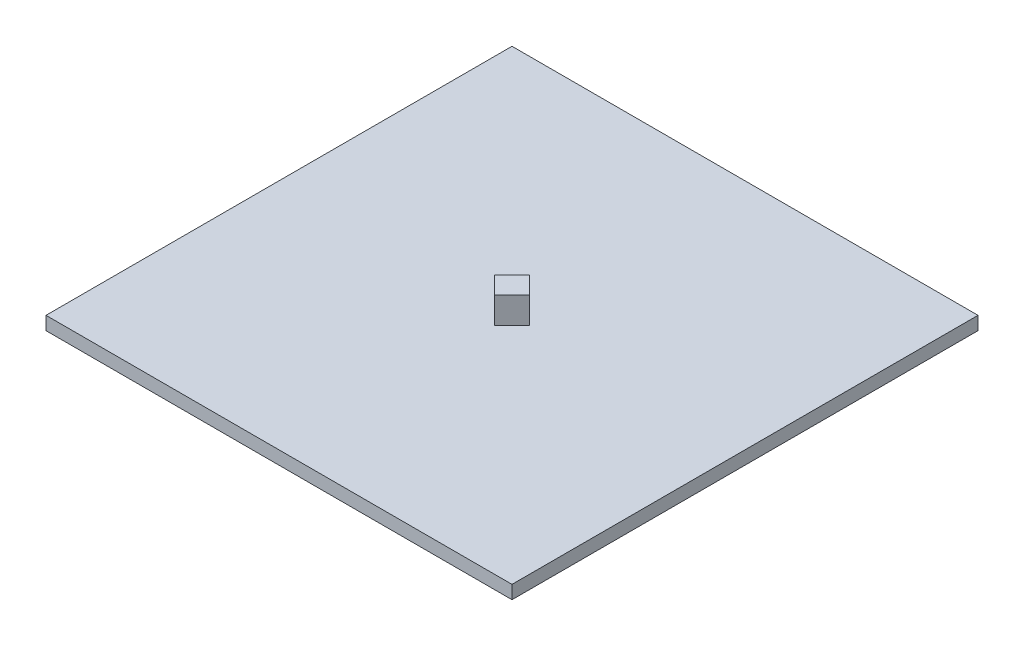
SolidWorks part; units mm, degrees
ref_plane "Front Plane" through (0, 0, 0) normal (0, 0, 1) x (1, 0, 0)
ref_plane "Top Plane" through (0, 0, 0) normal (0, 1, 0) x (1, 0, 0)
ref_plane "Right Plane" through (0, 0, 0) normal (1, 0, 0) x (0, 0, -1)
sketch "Sketch1" plane through (0, 0, 0) normal (0, 1, 0) x (1, 0, 0)
  line L1 (-44.45, -44.45) -> (44.45, -44.45)
  line L2 (-44.45, -44.45) -> (-44.45, 44.45)
  line L3 (-44.45, 44.45) -> (44.45, 44.45)
  line L4 (44.45, -44.45) -> (44.45, 44.45)
  line L5 (-44.45, -44.45) -> (44.45, 44.45) construction
  line L6 (-44.45, 44.45) -> (44.45, -44.45) construction
  point P0 (0, 0)
  dimension "D1" = 88.9
  dimension "D2" = 88.9
extrude "Boss-Extrude1" add sketch "Sketch1" along normal blind 2.54
sketch "Sketch2" plane through (0, 2.54, 0) normal (0, 1, 0) x (1, 0, 0)
  line L0 (0, 44.45) -> (0, -44.45) construction
  line L1 (0, -3.3588) -> (3.3588, 0)
  line L2 (0, -3.3588) -> (-3.3588, 0)
  line L3 (-3.3588, 0) -> (0, 3.3588)
  line L4 (3.3588, 0) -> (0, 3.3588)
  line L5 (0, -3.3588) -> (0, 3.3588) construction
  line L6 (-3.3588, 0) -> (3.3588, 0) construction
  line L7 (44.45, 44.45) -> (-44.45, 44.45) construction
  line L8 (-44.45, -44.45) -> (44.45, -44.45) construction
  point P0 (0, 0)
  point P6 (-1.7081, 13.0951)
  dimension "D1" = 4.75
extrude "Boss-Extrude2" add sketch "Sketch2" along normal blind 5
